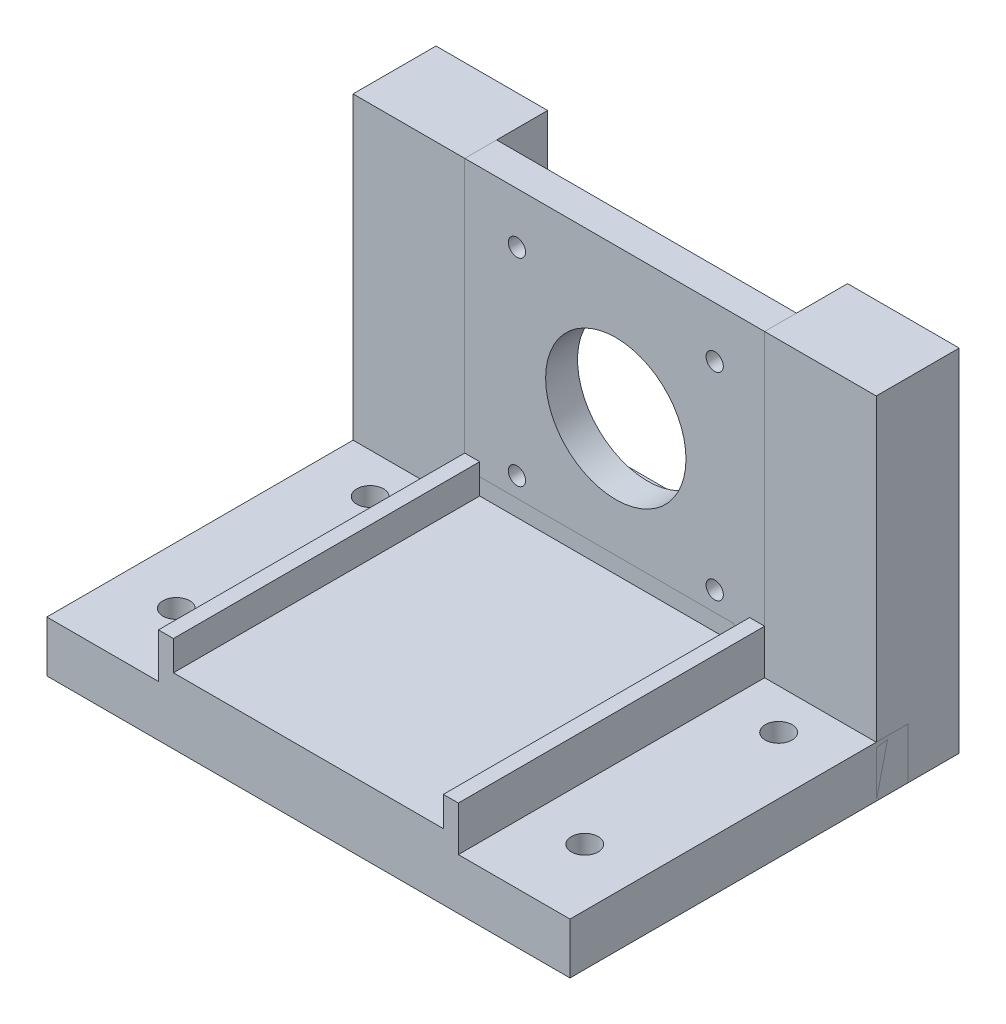
SolidWorks part; units mm, degrees
ref_plane "Спереди" through (0, 0, 0) normal (0, 0, 1) x (1, 0, 0)
ref_plane "Сверху" through (0, 0, 0) normal (0, 1, 0) x (1, 0, 0)
ref_plane "Справа" through (0, 0, 0) normal (1, 0, 0) x (0, 0, -1)
sketch "Эскиз1" plane through (0, 0, 0) normal (0, 0, 1) x (1, 0, 0)
  line L1 (-23.5, -23.5) -> (23.5, -23.5)
  line L2 (-23.5, -23.5) -> (-23.5, 23.5)
  line L3 (-23.5, 23.5) -> (23.5, 23.5)
  line L4 (23.5, -23.5) -> (23.5, 23.5)
  line L5 (-23.5, -23.5) -> (23.5, 23.5) construction
  line L6 (-23.5, 23.5) -> (23.5, -23.5) construction
  point P0 (0, 0)
extrude "Бобышка-Вытянуть1" add sketch "Эскиз1" along normal blind 53
sketch "Эскиз2" plane through (0, 0, 53) normal (0, 0, 1) x (1, 0, 0)
  line L1 (-21.15, -21.15) -> (21.15, -21.15)
  line L2 (-21.15, -21.15) -> (-21.15, 21.15)
  line L3 (-21.15, 21.15) -> (21.15, 21.15)
  line L4 (21.15, -21.15) -> (21.15, 21.15)
  line L5 (-21.15, -21.15) -> (21.15, 21.15) construction
  line L6 (-21.15, 21.15) -> (21.15, -21.15) construction
  point P0 (0, 0)
extrude "Вырез-Вытянуть1" cut sketch "Эскиз2" against normal blind 48
sketch "Эскиз3" plane through (0, 0, 5) normal (0, 0, 1) x (1, 0, 0)
  line L0 (0.1787, 0.0226) -> (0.1787, 35.5092) construction
  line L1 (0.1787, 0.0226) -> (-59.4946, 0.0226) construction
  circle A0 centre (0.1787, 0.0226) radius 11
  circle A1 centre (-15.3213, 15.5226) radius 1.35
  circle A2 centre (15.6787, 15.5226) radius 1.35
  circle A3 centre (15.6787, -15.4774) radius 1.35
  circle A4 centre (-15.3213, -15.4774) radius 1.35
extrude "Вырез-Вытянуть2" cut sketch "Эскиз3" against normal through all both and the other way through all
sketch "Эскиз7" plane through (23.5, 0, 0) normal (1, 0, 0) x (0, 0, -1)
  line L1 (-53, 23.5) -> (-5, 23.5)
  line L3 (-53, 23.5) -> (-53, -16.5)
  line L4 (-53, -16.5) -> (-5, -16.5)
  line L5 (-5, 23.5) -> (-5, -16.5)
extrude "Вырез-Вытянуть5" cut sketch "Эскиз7" against normal blind 47.5
sketch "Эскиз16" plane through (0, -23.5, 0) normal (0, -1, 0) x (1, 0, 0)
  line L0 (-23.5, 53) -> (-23.5, 0) construction
  line L1 (-23.5, 53) -> (23.5, 53)
  line L2 (-23.5, 53) -> (-23.5, 0)
  line L3 (-23.5, 0) -> (23.5, 0)
  line L4 (23.5, 53) -> (23.5, 0)
  line L5 (-23.5, 53) -> (23.5, 53) construction
extrude "Бобышка-Вытянуть4" add sketch "Эскиз16" along normal blind 8
sketch "Эскиз17" plane through (0, -31.5, 0) normal (0, -1, 0) x (1, 0, 0)
  line L0 (0, 53) -> (0, 0) construction
  line L1 (-32.0085, 53) -> (-32.0085, 21.9363) construction
  line L2 (-41, 0) -> (41, 0)
  line L3 (-41, 0) -> (-41, 53)
  line L4 (-41, 53) -> (41, 53)
  line L5 (41, 0) -> (41, 53)
  line L6 (-41, 0) -> (41, 53) construction
  line L7 (-41, 53) -> (41, 0) construction
  line L8 (0, 26.5) -> (-101.2271, 26.5) construction
  circle A0 centre (0, 0) radius 53 construction
  circle A1 centre (0, 53) radius 26.5 construction
  circle A3 centre (-23.5, 53) radius 8.5085 construction
  circle A4 centre (-32.0085, 26.5) radius 15.1925 construction
  circle A5 centre (-32.0085, 41.6925) radius 2.1
  circle A6 centre (-32.0085, 11.3075) radius 2.1
  circle A7 centre (32.0085, 11.3075) radius 2.1
  circle A8 centre (32.0085, 41.6925) radius 2.1
  point P7 (0, 26.5)
extrude "Бобышка-Вытянуть5" add sketch "Эскиз17" against normal blind 8
sketch "Эскиз22" plane through (0, 0, 0) normal (0, 0, -1) x (-1, 0, 0)
  line L0 (-23.5, 23.5) -> (23.5, 23.5) construction
  line L2 (-41, 23.5) -> (41, 23.5)
  line L3 (-41, 23.5) -> (-41, -31.5134)
  line L4 (-41, -31.5134) -> (41, -31.5134)
  line L5 (41, 23.5) -> (41, -31.5134)
  line L6 (-23.5, 23.5) -> (23.5, 23.5)
  line L7 (-23.5, 23.5) -> (-23.5, -18.5475)
  line L8 (-23.5, -18.5475) -> (23.5, -18.5475)
  line L9 (23.5, 23.5) -> (23.5, -18.5475)
  circle A0 centre (0, 23.5) radius 27.5 construction
  circle A1 centre (0, -4) radius 41 construction
  circle A2 centre (-41, -4) radius 27.5 construction
  circle A3 centre (41, -4) radius 27.5134 construction
extrude "Бобышка-Вытянуть17" add sketch "Эскиз22" along normal blind 8 and the other way up to surface (5 mm away) separate body
sketch "Эскиз24" plane through (0, 0, -8) normal (0, 0, -1) x (-1, 0, 0)
  line L0 (-23.1134, -17.0171) -> (23.8866, -17.0171) construction
  line L1 (0, -31.5) -> (0, 27.113) construction
  line L2 (-32.25, 23.5) -> (-32.25, -31.5) construction
  line L3 (-41, 23.5) -> (-23.5, 23.5) construction
  line L4 (-41, -31.5) -> (41, -31.5) construction
  circle A0 centre (-32.25, -0.4274) radius 6
  circle A1 centre (-32.25, -0.4274) radius 4.1
  circle A6 centre (32.25, -0.4274) radius 4.1
  circle A7 centre (32.25, -0.4274) radius 6
extrude "Вырез-Вытянуть6" cut sketch "Эскиз24" against normal blind 10 contours A1 | A6 | A0
